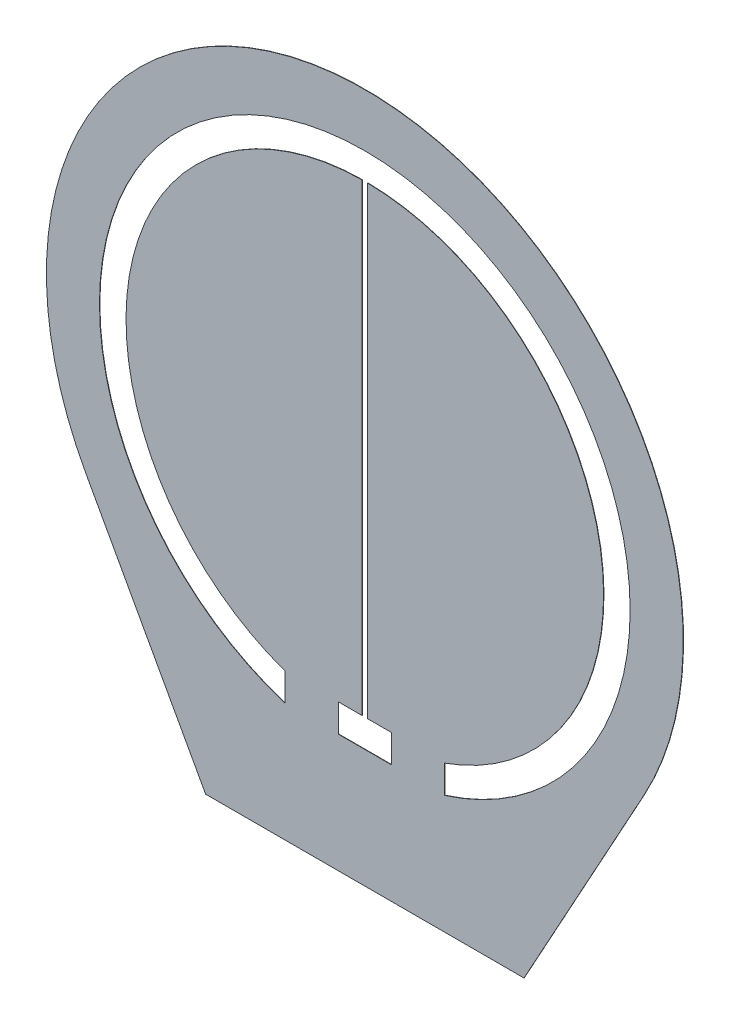
SolidWorks part; units mm, degrees
ref_plane "Plano frontal" through (0, 0, 0) normal (0, 0, 1) x (1, 0, 0)
ref_plane "Plano superior" through (0, 0, 0) normal (0, 1, 0) x (1, 0, 0)
ref_plane "Plano direito" through (0, 0, 0) normal (1, 0, 0) x (0, 0, -1)
sketch "Sketch2" plane through (0, 0, 0) normal (0, 0, 1) x (1, 0, 0)
  line L0 (0.25, -21.2132) -> (2.5, -21.2132)
  line L1 (0, -35) -> (-15, -35)
  line L2 (-15, -35) -> (-7.5, -35)
  line L3 (-7.5, -21.2132) -> (-7.5, -23.8485)
  line L4 (-2.5, -21.2132) -> (-0.25, -21.2132)
  line L5 (7.5, -21.2132) -> (7.5, -23.8485)
  line L6 (7.5, -35) -> (0, -35)
  line L8 (-0.25, -21.2132) -> (-0.25, 22.4986)
  line L9 (0.25, -21.2132) -> (0.25, 22.4986)
  line L10 (-15, -35) -> (-26.2929, -14.4459)
  line L11 (15, -35) -> (26.2929, -14.4459)
  line L13 (-2.5, -21.2132) -> (-2.5, -23.8485)
  line L14 (2.5, -21.2132) -> (2.5, -23.8485)
  line L15 (-2.5, -23.8485) -> (2.5, -23.8485)
  line L20 (0, -35) -> (15, -35)
  arc A0 (-0.25, 22.4986) -> (-7.5, -21.2132) centre (0, 0) ccw
  arc A2 (7.5, -21.2132) -> (0.25, 22.4986) centre (0, 0) ccw
  arc A3 (7.5, -23.8485) -> (-7.5, -23.8485) centre (0, 0) ccw
  arc A4 (26.2929, -14.4459) -> (-26.2929, -14.4459) centre (0, 0) ccw
  point P14 (0, -21.2132)
  dimension "D1" = 45
  dimension "D3" = 50
  dimension "D11" = 60
  dimension "D4" = 15
  dimension "D5" = 0.5
  dimension "D6" = 5
  dimension "D7" = 5
  dimension "D8" = 2.6353
  dimension "D9" = 2.6353
  dimension "D10" = 15
extrude "Boss-Extrude1" add sketch "Sketch2" along normal blind 0.0356
